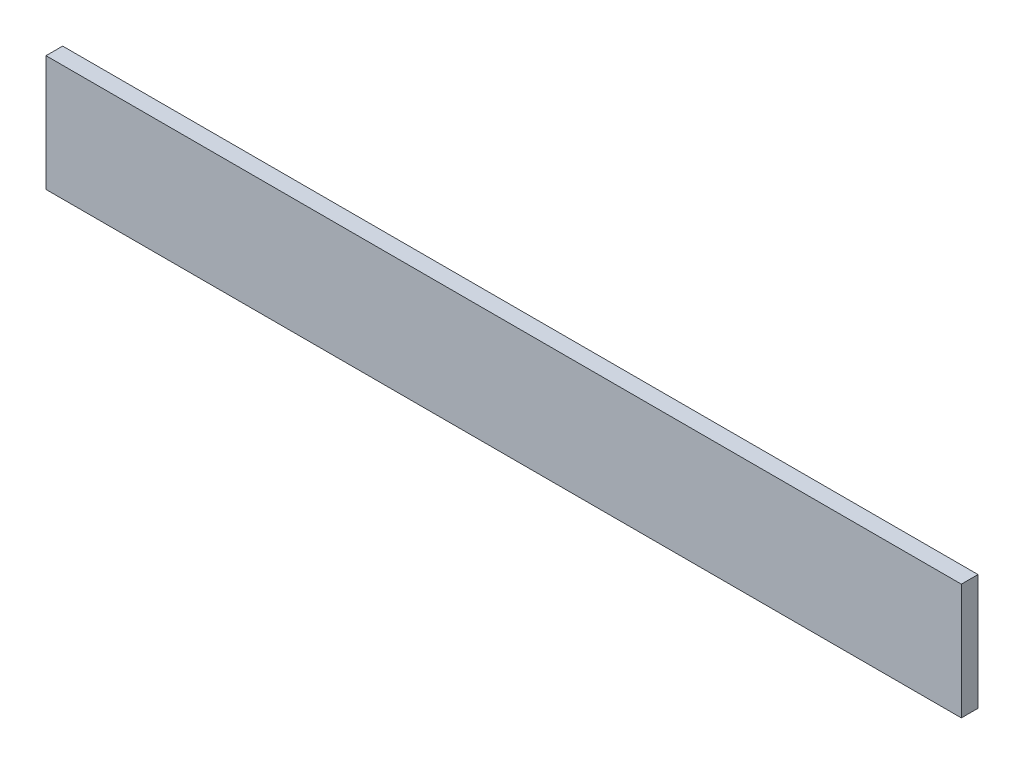
SolidWorks part; units mm, degrees
material "Pine"
ref_plane "Front Plane" through (0, 0, 0) normal (0, 0, 1) x (1, 0, 0)
ref_plane "Top Plane" through (0, 0, 0) normal (0, 1, 0) x (1, 0, 0)
ref_plane "Right Plane" through (0, 0, 0) normal (1, 0, 0) x (0, 0, -1)
sketch "Sketch1" plane through (0, 0, 0) normal (0, 0, 1) x (1, 0, 0)
  line L1 (-501.65, 63.5) -> (501.65, 63.5)
  line L2 (-501.65, 63.5) -> (-501.65, -63.5)
  line L3 (-501.65, -63.5) -> (501.65, -63.5)
  line L4 (501.65, 63.5) -> (501.65, -63.5)
  line L5 (-501.65, 63.5) -> (501.65, -63.5) construction
  line L6 (-501.65, -63.5) -> (501.65, 63.5) construction
  point P0 (0, 0)
  dimension "D1" = 1003.3
  dimension "D2" = 127
extrude "Boss-Extrude1" add sketch "Sketch1" along normal blind 18.2562
